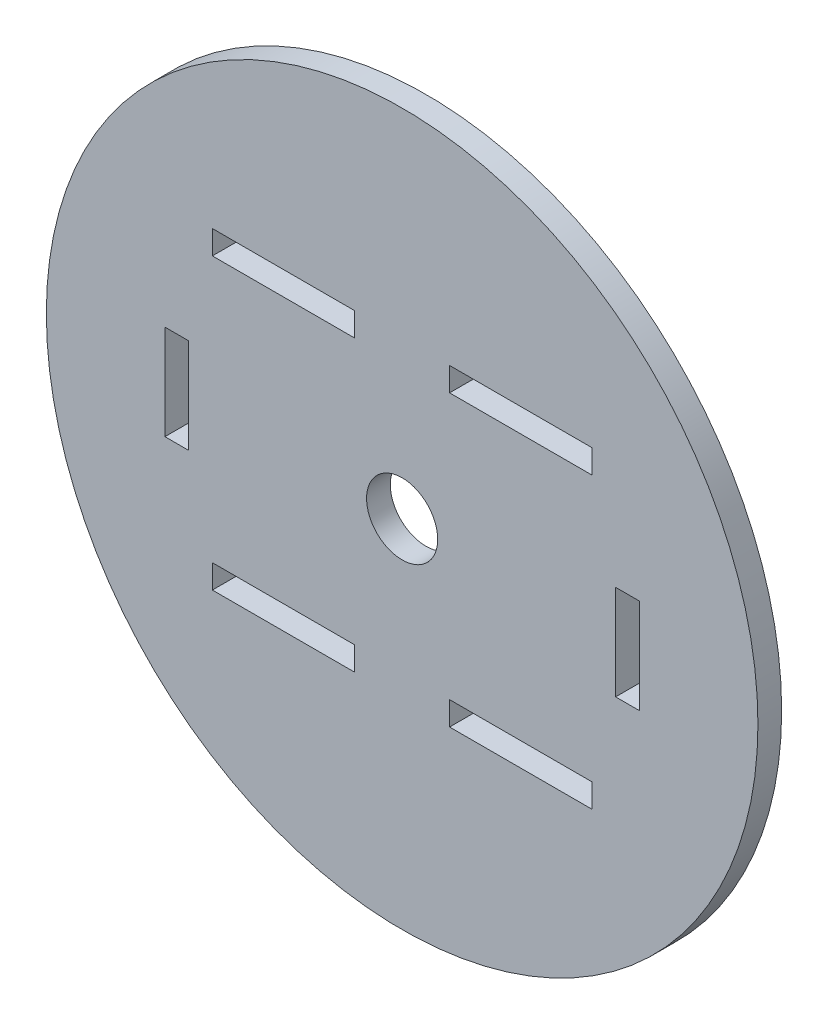
SolidWorks part; units mm, degrees
ref_plane "Front Plane" through (0, 0, 0) normal (0, 0, 1) x (1, 0, 0)
ref_plane "Top Plane" through (0, 0, 0) normal (0, 1, 0) x (1, 0, 0)
ref_plane "Right Plane" through (0, 0, 0) normal (1, 0, 0) x (0, 0, -1)
sketch "Sketch1" plane through (0, 0, 0) normal (0, 0, 1) x (1, 0, 0)
  circle A0 centre (0, 0) radius 47.625
  circle A1 centre (0, 0) radius 4.7625
  dimension "D1" = 95.25
  dimension "D2" = 9.525
extrude "Boss-Extrude1" add sketch "Sketch1" along normal blind 3.175
sketch "Sketch3" plane through (0, 0, 0) normal (0, 0, 1) x (1, 0, 0)
  line L0 (0, 0) -> (-25.4, 0) construction
  line L1 (-28.575, 0) -> (-28.575, -6.35)
  line L2 (-28.575, 0) -> (-28.575, 6.35)
  line L3 (-28.575, -6.35) -> (-31.75, -6.35)
  line L4 (-31.75, -6.35) -> (-31.75, 6.35)
  line L5 (-31.75, 6.35) -> (-28.575, 6.35)
  line L6 (0, 0) -> (0, 17.78) construction
  line L7 (0, 0) -> (31.75, 0) construction
  line L8 (31.75, 0) -> (31.75, 6.35)
  line L9 (31.75, 0) -> (31.75, -6.35)
  line L10 (31.75, -6.35) -> (28.575, -6.35)
  line L11 (28.575, -6.35) -> (28.575, 6.35)
  line L12 (28.575, 6.35) -> (31.75, 6.35)
  line L13 (0, 17.78) -> (6.35, 17.78) construction
  line L14 (0, 17.78) -> (-6.35, 17.78) construction
  line L15 (0, 0) -> (25.4, 0) construction
  line L16 (6.35, 17.78) -> (25.4, 17.78)
  line L17 (6.35, 17.78) -> (6.35, 20.955)
  line L18 (6.35, 20.955) -> (25.4, 20.955)
  line L19 (25.4, 17.78) -> (25.4, 20.955)
  line L24 (-25.4, 0) -> (-25.4, 17.78) construction
  line L25 (-25.4, 0) -> (-25.4, -20.955) construction
  line L26 (-25.4, 17.78) -> (-6.35, 17.78)
  line L27 (-25.4, 17.78) -> (-25.4, 20.955)
  line L28 (-25.4, 20.955) -> (-6.35, 20.955)
  line L29 (-6.35, 17.78) -> (-6.35, 20.955)
  line L30 (-6.35, -20.955) -> (6.35, -20.955) construction
  line L35 (-25.4, -20.955) -> (-6.35, -20.955)
  line L40 (-25.4, -20.955) -> (-25.4, -17.78)
  line L41 (-25.4, -17.78) -> (-6.35, -17.78)
  line L42 (-6.35, -20.955) -> (-6.35, -17.78)
  line L44 (6.35, -20.955) -> (25.4, -20.955)
  line L45 (6.35, -20.955) -> (6.35, -17.78)
  line L46 (6.35, -17.78) -> (25.4, -17.78)
  line L47 (25.4, -20.955) -> (25.4, -17.78)
  dimension "D2" = 28.575
  dimension "D3" = 28.575
extrude "Cut-Extrude2" cut sketch "Sketch3" along normal blind 3.175
